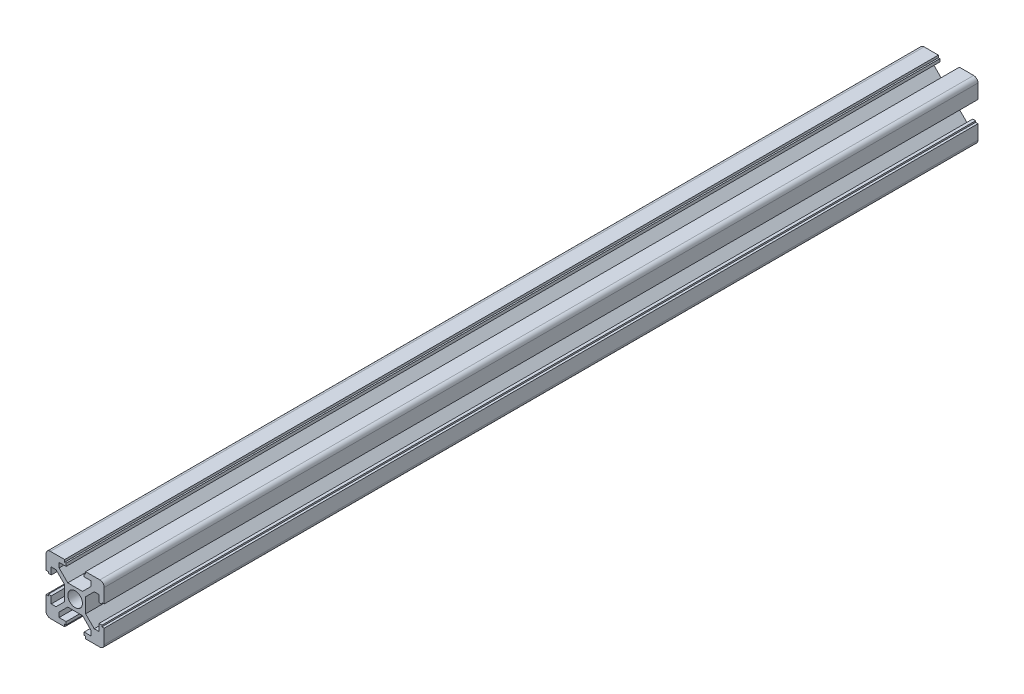
SolidWorks part; units mm, degrees
ref_plane "前视基准面" through (0, 0, 0) normal (0, 0, 1) x (1, 0, 0)
ref_plane "上视基准面" through (0, 0, 0) normal (0, 1, 0) x (1, 0, 0)
ref_plane "右视基准面" through (0, 0, 0) normal (1, 0, 0) x (0, 0, -1)
other "Configuration Table"
sketch "草图2" plane through (0, 0, 0) normal (0, 0, 1) x (1, 0, 0)
  line L0 (-5.8258, 3.4539) -> (-5.8258, 6.5539) construction
  line L1 (-5.8258, 5.9932) -> (-5.8258, 0.9145)
  line L2 (0.3135, 7.0539) -> (-4.7652, 7.0539)
  line L3 (1.3742, 0.9145) -> (1.3742, 5.9932)
  line L4 (-4.7652, -0.1461) -> (0.3135, -0.1461)
  line L5 (-12.2258, 3.4539) -> (7.7742, 3.4539) construction
  line L6 (-2.2258, 13.4539) -> (-2.2258, -6.5461) construction
  line L7 (-12.2258, 13.4539) -> (-2.2258, 3.4539) construction
  line L8 (-12.2258, 7.0539) -> (-5.8258, 7.0539) construction
  line L9 (-11.4258, 6.5539) -> (-5.3258, 6.5539) construction
  line L10 (-10.4258, 8.9539) -> (-7.7258, 8.9539) construction
  line L11 (-8.7865, 8.9539) -> (-5.8258, 5.9932) construction
  line L12 (-12.2258, 11.9539) -> (-12.2258, 7.0539)
  line L13 (-12.2258, 7.0539) -> (-11.4258, 7.0539)
  line L14 (-11.4258, 7.0539) -> (-11.4258, 6.5539)
  line L15 (-11.4258, 6.5539) -> (-10.4258, 6.5539)
  line L16 (-10.4258, 6.5539) -> (-10.4258, 8.9539)
  line L17 (-10.4258, 8.9539) -> (-8.7865, 8.9539)
  line L18 (-8.7865, 8.9539) -> (-5.8258, 5.9932)
  line L19 (-5.3258, 12.6539) -> (-5.3258, 11.6539)
  line L20 (-5.8258, 12.6539) -> (-5.3258, 12.6539)
  line L21 (-5.8258, 13.4539) -> (-5.8258, 12.6539)
  line L22 (-10.7258, 13.4539) -> (-5.8258, 13.4539)
  line L23 (-5.3258, 11.6539) -> (-7.7258, 11.6539)
  line L24 (-7.7258, 11.6539) -> (-7.7258, 10.0145)
  line L25 (-7.7258, 10.0145) -> (-4.7652, 7.0539)
  line L26 (7.7742, 13.4539) -> (-2.2258, 3.4539) construction
  line L27 (3.2742, 10.0145) -> (0.3135, 7.0539)
  line L28 (3.2742, 11.6539) -> (3.2742, 10.0145)
  line L29 (0.8742, 11.6539) -> (3.2742, 11.6539)
  line L30 (0.8742, 12.6539) -> (0.8742, 11.6539)
  line L31 (1.3742, 12.6539) -> (0.8742, 12.6539)
  line L32 (1.3742, 13.4539) -> (1.3742, 12.6539)
  line L33 (6.2742, 13.4539) -> (1.3742, 13.4539)
  line L34 (7.7742, 11.9539) -> (7.7742, 7.0539)
  line L35 (7.7742, 7.0539) -> (6.9742, 7.0539)
  line L36 (6.9742, 7.0539) -> (6.9742, 6.5539)
  line L37 (6.9742, 6.5539) -> (5.9742, 6.5539)
  line L38 (5.9742, 6.5539) -> (5.9742, 8.9539)
  line L39 (5.9742, 8.9539) -> (4.3348, 8.9539)
  line L40 (4.3348, 8.9539) -> (1.3742, 5.9932)
  line L41 (7.7742, -6.5461) -> (-2.2258, 3.4539) construction
  line L42 (4.3348, -2.0461) -> (1.3742, 0.9145)
  line L43 (5.9742, -2.0461) -> (4.3348, -2.0461)
  line L44 (5.9742, 0.3539) -> (5.9742, -2.0461)
  line L45 (6.9742, 0.3539) -> (5.9742, 0.3539)
  line L46 (6.9742, -0.1461) -> (6.9742, 0.3539)
  line L47 (7.7742, -0.1461) -> (6.9742, -0.1461)
  line L48 (7.7742, -5.0461) -> (7.7742, -0.1461)
  line L49 (6.2742, -6.5461) -> (1.3742, -6.5461)
  line L50 (1.3742, -6.5461) -> (1.3742, -5.7461)
  line L51 (1.3742, -5.7461) -> (0.8742, -5.7461)
  line L52 (0.8742, -5.7461) -> (0.8742, -4.7461)
  line L53 (0.8742, -4.7461) -> (3.2742, -4.7461)
  line L54 (3.2742, -4.7461) -> (3.2742, -3.1068)
  line L55 (3.2742, -3.1068) -> (0.3135, -0.1461)
  line L56 (-12.2258, -6.5461) -> (-2.2258, 3.4539) construction
  line L57 (-7.7258, -3.1068) -> (-4.7652, -0.1461)
  line L58 (-7.7258, -4.7461) -> (-7.7258, -3.1068)
  line L59 (-5.3258, -4.7461) -> (-7.7258, -4.7461)
  line L60 (-5.3258, -5.7461) -> (-5.3258, -4.7461)
  line L61 (-5.8258, -5.7461) -> (-5.3258, -5.7461)
  line L62 (-5.8258, -6.5461) -> (-5.8258, -5.7461)
  line L63 (-10.7258, -6.5461) -> (-5.8258, -6.5461)
  line L64 (-12.2258, -5.0461) -> (-12.2258, -0.1461)
  line L65 (-12.2258, -0.1461) -> (-11.4258, -0.1461)
  line L66 (-11.4258, -0.1461) -> (-11.4258, 0.3539)
  line L67 (-11.4258, 0.3539) -> (-10.4258, 0.3539)
  line L68 (-10.4258, 0.3539) -> (-10.4258, -2.0461)
  line L69 (-10.4258, -2.0461) -> (-8.7865, -2.0461)
  line L70 (-8.7865, -2.0461) -> (-5.8258, 0.9145)
  arc A0 (-12.2258, 11.9539) -> (-10.7258, 13.4539) centre (-10.7258, 11.9539) cw
  circle A1 centre (-2.2258, 3.4539) radius 2.5
  arc A2 (6.2742, 13.4539) -> (7.7742, 11.9539) centre (6.2742, 11.9539) cw
  arc A3 (7.7742, -5.0461) -> (6.2742, -6.5461) centre (6.2742, -5.0461) cw
  arc A4 (-10.7258, -6.5461) -> (-12.2258, -5.0461) centre (-10.7258, -5.0461) cw
  point P13 (-2.2258, 3.4539)
  point P84 (-2.2258, 3.4539)
  dimension "D8" = 1.5
  dimension "D9" = 5
  dimension "D1" = 20
  dimension "D2" = 6.2
  dimension "D3" = 7.2
  dimension "D4" = 11
  dimension "D5" = 1.5
  dimension "D6" = 0.8
  dimension "D7" = 1.8
  dimension "D10" = 7.2
extrude "凸台-拉伸1" add sketch "草图2" along normal blind 300
